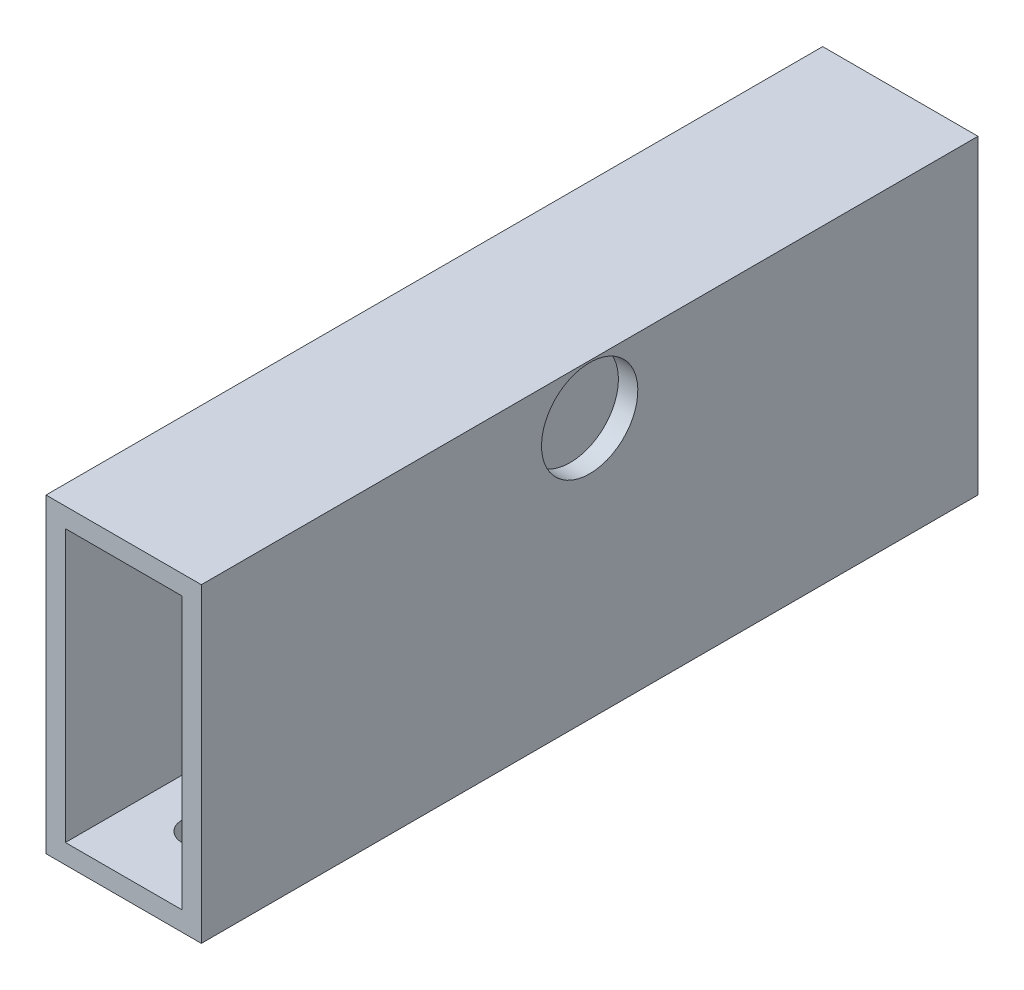
SolidWorks part; units mm, degrees
ref_plane "Front Plane" through (0, 0, 0) normal (0, 0, 1) x (1, 0, 0)
ref_plane "Top Plane" through (0, 0, 0) normal (0, 1, 0) x (1, 0, 0)
ref_plane "Right Plane" through (0, 0, 0) normal (1, 0, 0) x (0, 0, -1)
sketch "Sketch1" plane through (0, 0, 0) normal (0, 0, 1) x (1, 0, 0)
  line L0 (-8.9426, 17.1332) -> (10.1074, 17.1332)
  line L1 (-12.1176, 20.3082) -> (13.2824, 20.3082)
  line L2 (-12.1176, 20.3082) -> (-12.1176, -30.4918)
  line L3 (-12.1176, -30.4918) -> (13.2824, -30.4918)
  line L4 (13.2824, 20.3082) -> (13.2824, -30.4918)
  line L5 (10.1074, 17.1332) -> (10.1074, -27.3168)
  line L6 (-8.9426, -27.3168) -> (10.1074, -27.3168)
  line L7 (-8.9426, 17.1332) -> (-8.9426, -27.3168)
  dimension "D1" = 25.4
  dimension "D2" = 50.8
  dimension "D3" = 3.175
extrude "Boss-Extrude1" add sketch "Sketch1" along normal mid plane 127
sketch "Sketch2" plane through (-12.1176, 0, 0) normal (-1, 0, 0) x (0, 0, 1)
  line L0 (63.5, 20.3082) -> (63.5, -30.4918) construction
  line L1 (63.5, -30.4918) -> (-63.5, -30.4918) construction
  circle A0 centre (0, 12.1381) radius 7.874
  dimension "D1" = 63.5
  dimension "D2" = 42.6298
extrude "Cut-Extrude1" cut sketch "Sketch2" against normal blind 25.4
sketch "Sketch3" plane through (0, -30.4918, 0) normal (0, -1, 0) x (1, 0, 0)
  line L0 (13.2824, 63.5) -> (13.2824, -63.5) construction
  line L1 (-12.1176, 63.5) -> (13.2824, 63.5) construction
  line L2 (-12.1176, 63.5) -> (-12.1176, -63.5) construction
  line L3 (-12.1176, -63.5) -> (13.2824, -63.5) construction
  circle A0 centre (0.5824, 50.8) radius 3.175
  circle A1 centre (0.5824, -50.8) radius 3.175
  point P12 (1.0028, 10.9687)
  dimension "D1" = 12.7
  dimension "D3" = 12.7
  dimension "D2" = 12.7
  dimension "D4" = 12.7
extrude "Cut-Extrude2" cut sketch "Sketch3" against normal blind 3.175
